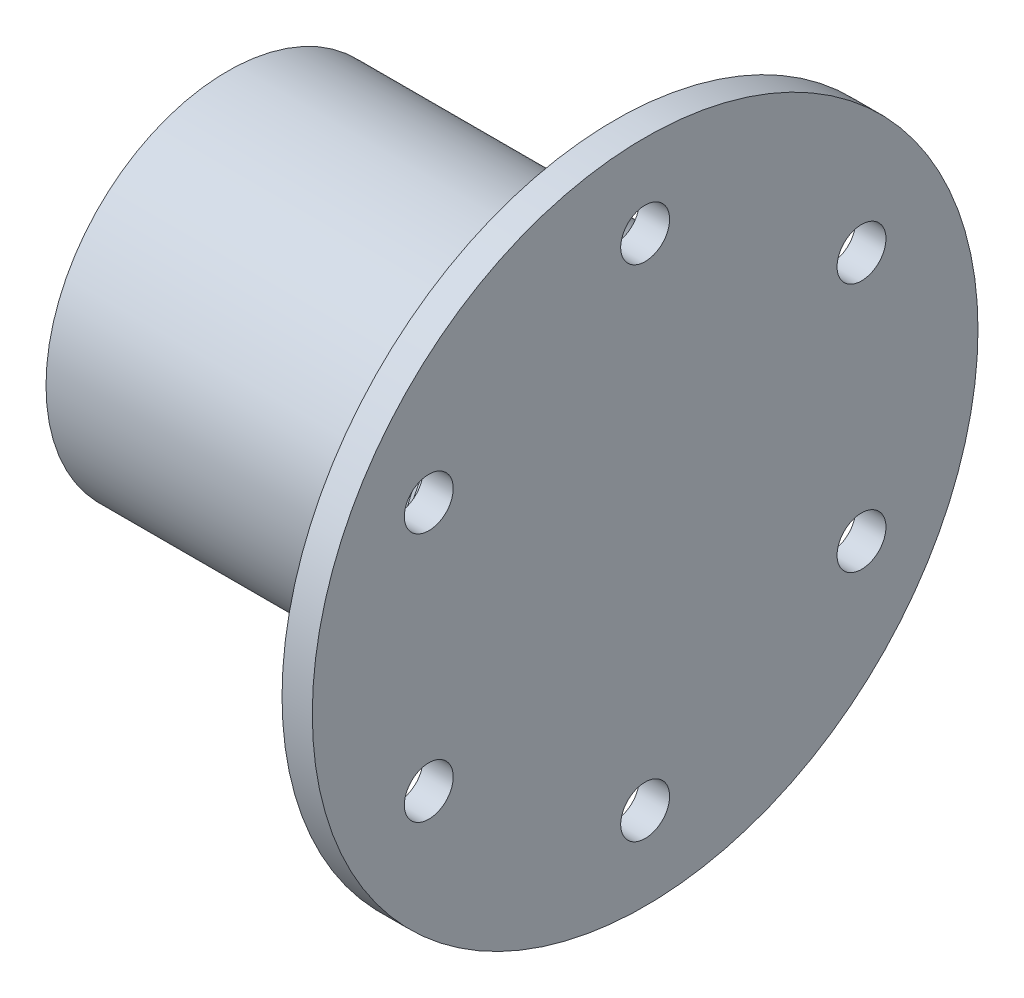
SolidWorks part; units mm, degrees
material "6061-T6 (SS)"
ref_plane "Front Plane" through (0, 0, 0) normal (0, 0, 1) x (1, 0, 0)
ref_plane "Top Plane" through (0, 0, 0) normal (0, 1, 0) x (1, 0, 0)
ref_plane "Right Plane" through (0, 0, 0) normal (1, 0, 0) x (0, 0, -1)
sketch "Sketch1" plane through (0, 0, 0) normal (1, 0, 0) x (0, 0, -1)
  line L0 (0, 0) -> (0, 20.64) construction
  arc A0 (-1.6237, 23.2194) -> (1.6237, -23.2194) centre (0, 0) ccw construction
  arc A1 (1.0588, 18.9205) -> (-1.0588, 22.3595) centre (0, 20.64) ccw construction
  circle A2 centre (0, 0) radius 27.5
  circle A3 centre (0, 20.64) radius 2.0193
  circle A4 centre (17.8748, 10.32) radius 2.0193
  circle A5 centre (17.8748, -10.32) radius 2.0193
  circle A6 centre (0, -20.64) radius 2.0193
  circle A7 centre (-17.8748, -10.32) radius 2.0193
  circle A8 centre (-17.8748, 10.32) radius 2.0193
  circle A9 centre (0, 0) radius 17.46 construction
  point P21 (0, 0)
  dimension "D1" = 23.2761
  dimension "D2" = 2.0193
  dimension "D3" = 20.64
  dimension "D5" = 34.92
  dimension "D6" = 55
  dimension "D4" = 6
extrude "Boss-Extrude1" add sketch "Sketch1" along normal blind 2.5
sketch "Sketch2" plane through (0, 0, 0) normal (-1, 0, 0) x (0, 0, 1)
  circle A0 centre (0, 0) radius 17.46 construction
  circle A1 centre (0, 0) radius 17.46
extrude "Boss-Extrude2" add sketch "Sketch2" along normal blind 2
chamfer "Chamfer5" distance 1 angle 45 1 edges at (-2, 0, 17.46)
sketch "Sketch6" plane through (-2, 0, 0) normal (1, 0, 0) x (0, 0, -1)
  line L0 (0, 11.1803) -> (0, -11.1803) construction
  line L5 (-10, -11.1803) -> (10, 11.1803) construction
  line L6 (-10, 11.1803) -> (10, -11.1803) construction
  circle A1 centre (0, 0) radius 15
  dimension "D1" = 30
  dimension "D2" = 20
extrude "Boss-Extrude3" add sketch "Sketch6" against normal blind 30
